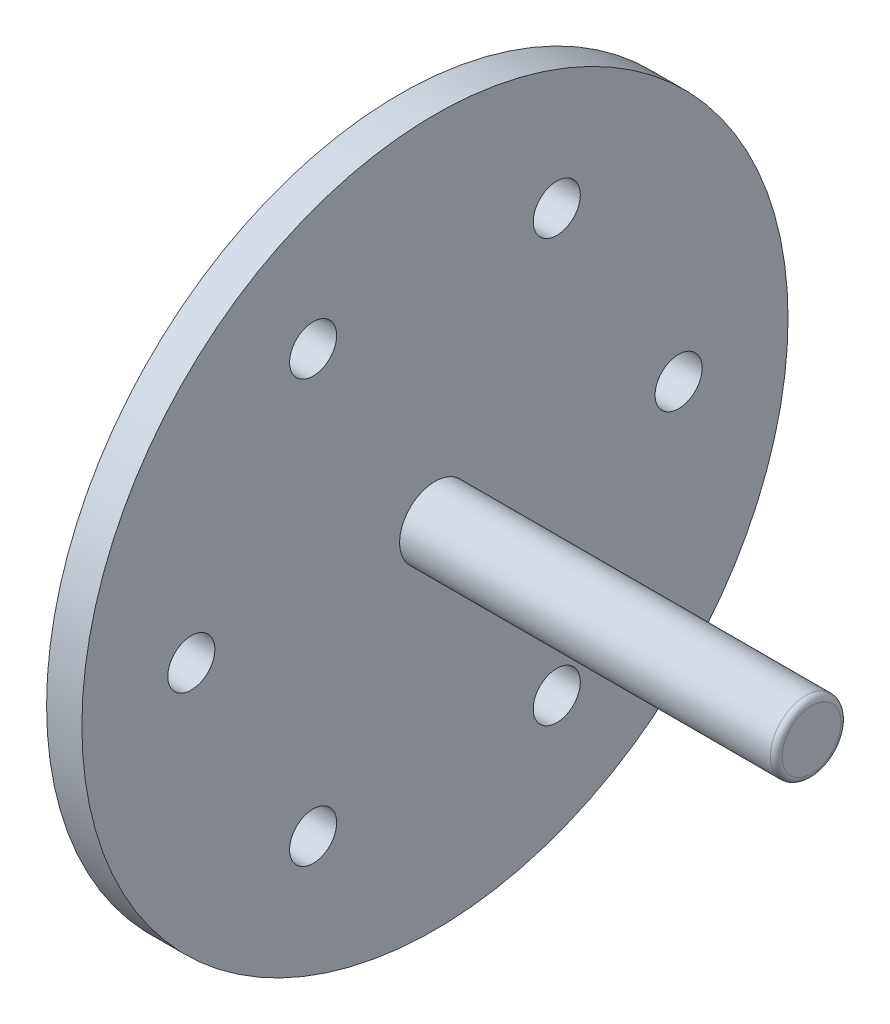
SolidWorks part; units mm, degrees
material "1023 Carbon Steel Sheet (SS)"
ref_plane "Front Plane" through (0, 0, 0) normal (0, 0, 1) x (1, 0, 0)
ref_plane "Top Plane" through (0, 0, 0) normal (0, 1, 0) x (1, 0, 0)
ref_plane "Right Plane" through (0, 0, 0) normal (1, 0, 0) x (0, 0, -1)
sketch "Sketch1" plane through (0, 0, 0) normal (1, 0, 0) x (0, 0, -1)
  circle A0 centre (0, 0) radius 30
  point P3 (0, 0)
  point P6 (0, 0)
  dimension "D1" = 60
extrude "Boss-Extrude1" add sketch "Sketch1" along normal blind 3
sketch "Sketch2" plane through (0, 0, 0) normal (1, 0, 0) x (0, 0, -1)
  circle A2 centre (20.7, 0) radius 2
  circle A3 centre (10.35, -17.9267) radius 2
  circle A4 centre (-10.35, -17.9267) radius 2
  circle A5 centre (-20.7, 0) radius 2
  circle A6 centre (-10.35, 17.9267) radius 2
  circle A7 centre (10.35, 17.9267) radius 2
  dimension "D1" = 4
  dimension "D2" = 20.7
  dimension "D3" = 6
extrude "Cut-Extrude1" cut sketch "Sketch2" along normal up to surface (3 mm away) up to face at (3, 0, -30)
sketch "Sketch3" plane through (3, 0, 0) normal (1, 0, 0) x (0, 0, -1)
  circle A0 centre (0, 0) radius 3
  dimension "D1" = 6
extrude "Boss-Extrude2" add sketch "Sketch3" along normal blind 32
fillet "Fillet1" radius 0.5 1 edges at (35, 0, -3)
